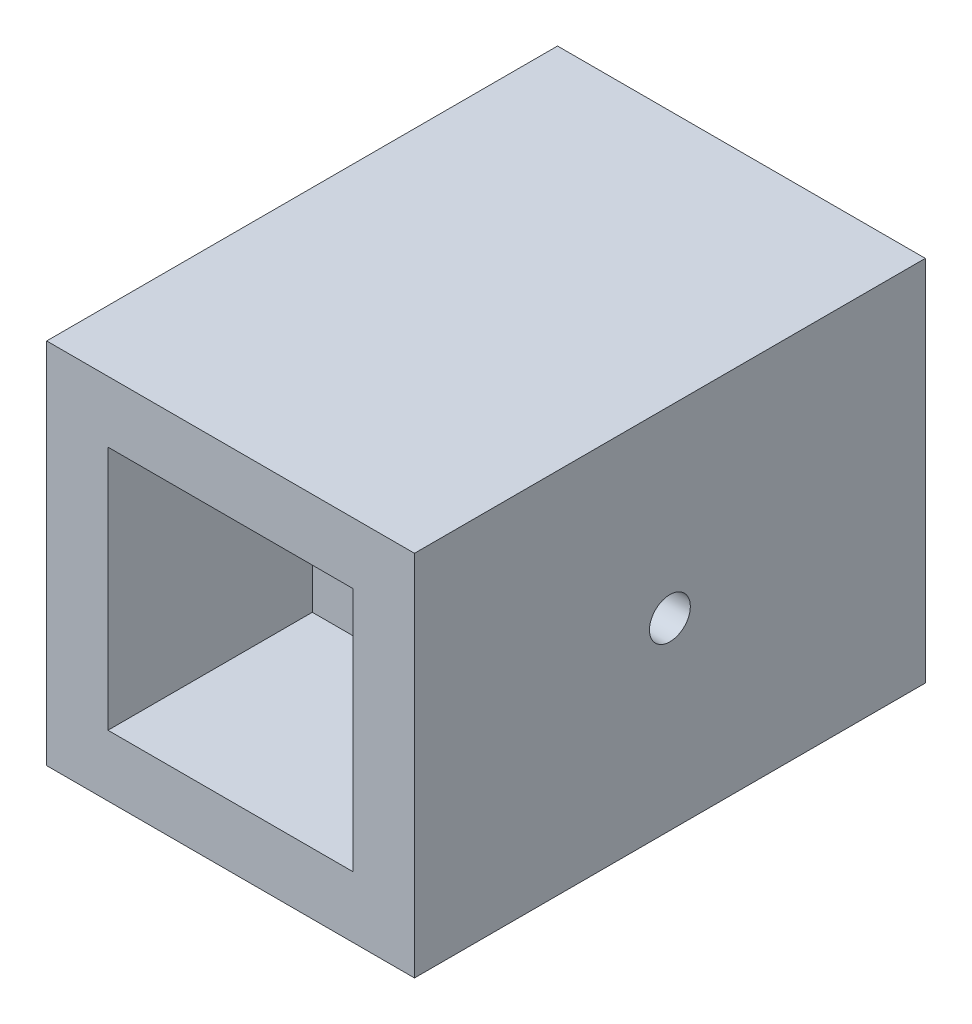
SolidWorks part; units mm, degrees
ref_plane "前视基准面" through (0, 0, 0) normal (0, 0, 1) x (1, 0, 0)
ref_plane "上视基准面" through (0, 0, 0) normal (0, 1, 0) x (1, 0, 0)
ref_plane "右视基准面" through (0, 0, 0) normal (1, 0, 0) x (0, 0, -1)
sketch "草图1" plane through (0, 0, 0) normal (0, 0, 1) x (1, 0, 0)
  line L1 (0, 0) -> (18, 0)
  line L2 (0, 0) -> (0, 18)
  line L3 (0, 18) -> (18, 18)
  line L4 (18, 0) -> (18, 18)
  point P5 (0, 0)
  point P6 (0, 0)
extrude "凸台-拉伸2" add sketch "草图1" along normal blind 25
sketch "草图2" plane through (0, 0, 0) normal (0, 0, -1) x (-1, 0, 0)
  line L1 (-3, 3) -> (-15, 3)
  line L2 (-3, 3) -> (-3, 15)
  line L3 (-3, 15) -> (-15, 15)
  line L4 (-15, 3) -> (-15, 15)
  point P0 (-3, 3)
  point P5 (0, 0)
  point P6 (0, 0)
  point P7 (0, 0)
extrude "切除-拉伸1" cut sketch "草图2" against normal blind 10
sketch "草图3" plane through (18, 0, 0) normal (1, 0, 0) x (0, 0, -1)
  circle A0 centre (-12.5, 7) radius 1
  point P0 (-12.5, 7)
sketch "草图4" plane through (0, 0, 25) normal (0, 0, 1) x (1, 0, 0)
  line L1 (3, 3) -> (15, 3)
  line L2 (3, 3) -> (3, 15)
  line L3 (3, 15) -> (15, 15)
  line L4 (15, 3) -> (15, 15)
  point P0 (3, 3)
  point P5 (0, 0)
  point P6 (0, 0)
extrude "切除-拉伸3" cut sketch "草图4" against normal blind 10
sketch "草图5" plane through (18, 0, 0) normal (1, 0, 0) x (0, 0, -1)
  circle A0 centre (-12.5, 9) radius 1
  point P0 (-12.5, 9)
extrude "切除-拉伸4" cut sketch "草图5" against normal blind 18
